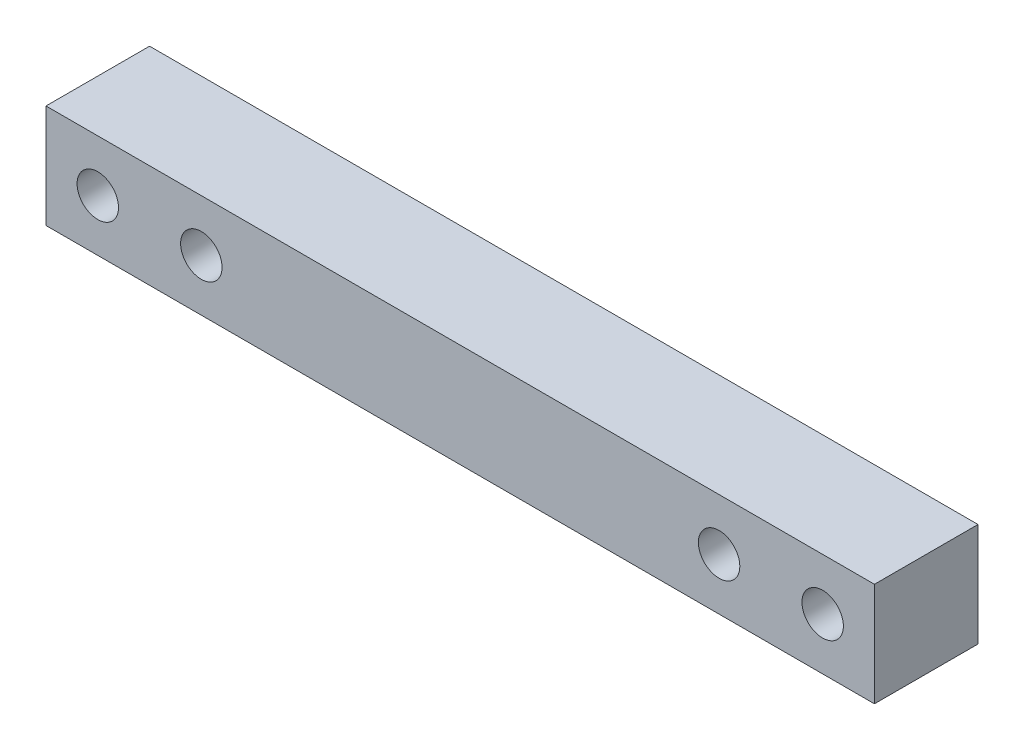
SolidWorks part; units mm, degrees
ref_plane "前视基准面" through (0, 0, 0) normal (0, 0, 1) x (1, 0, 0)
ref_plane "上视基准面" through (0, 0, 0) normal (0, 1, 0) x (1, 0, 0)
ref_plane "右视基准面" through (0, 0, 0) normal (1, 0, 0) x (0, 0, -1)
sketch "草图1" plane through (0, 0, 0) normal (0, 0, 1) x (1, 0, 0)
  line L1 (40, -5) -> (-40, -5)
  line L2 (40, -5) -> (40, 5)
  line L3 (40, 5) -> (-40, 5)
  line L4 (-40, -5) -> (-40, 5)
  line L5 (40, -5) -> (-40, 5) construction
  line L6 (40, 5) -> (-40, -5) construction
  point P0 (0, 0)
  dimension "D1" = 80
  dimension "D2" = 10
extrude "凸台-拉伸1" add sketch "草图1" along normal blind 10
sketch "草图2" plane through (0, 0, 10) normal (0, 0, 1) x (1, 0, 0)
  line L0 (-40, 5) -> (-40, -5) construction
  line L1 (40, -5) -> (40, 5) construction
  circle A0 centre (-35, 0) radius 2
  circle A1 centre (35, 0) radius 2
  circle A2 centre (-25, 0) radius 2
  circle A3 centre (25, 0) radius 2
  dimension "D1" = 4
  dimension "D2" = 4
  dimension "D3" = 4
  dimension "D4" = 4
  dimension "D5" = 10
  dimension "D6" = 10
  dimension "D7" = 5
  dimension "D8" = 5
extrude "切除-拉伸1" cut sketch "草图2" against normal blind 10
